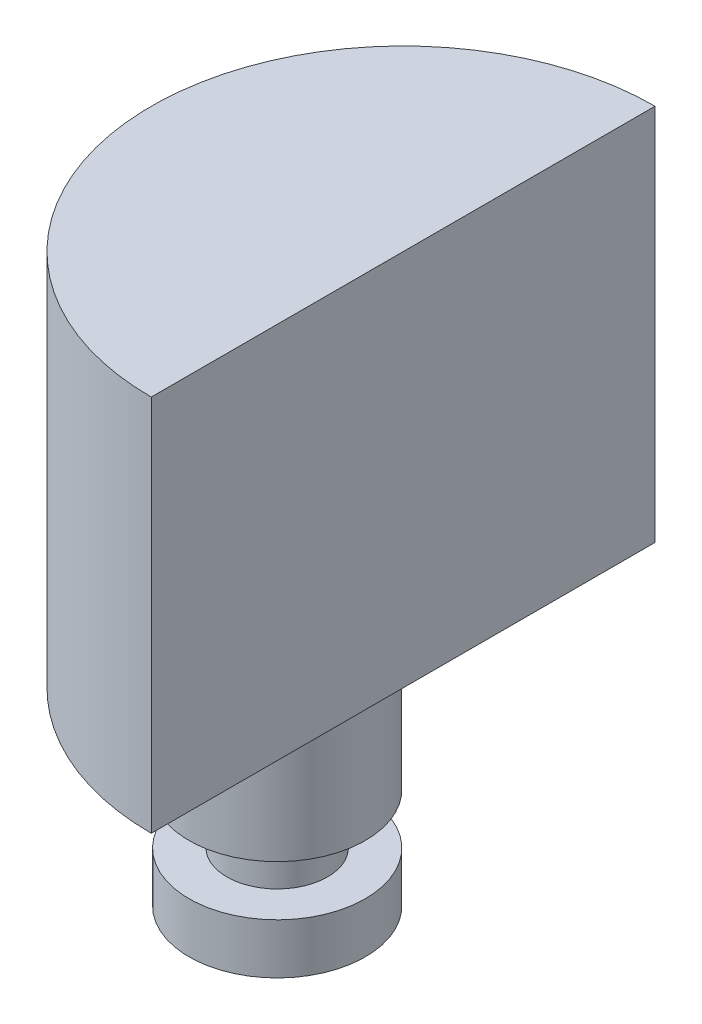
SolidWorks part; units mm, degrees
ref_plane "Alzado" through (0, 0, 0) normal (0, 0, 1) x (1, 0, 0)
ref_plane "Planta" through (0, 0, 0) normal (0, 1, 0) x (1, 0, 0)
ref_plane "Vista lateral" through (0, 0, 0) normal (1, 0, 0) x (0, 0, -1)
sketch "Croquis2" plane through (0, 0, 0) normal (0, 1, 0) x (1, 0, 0)
  line L0 (0, 10) -> (0, -10)
  arc A0 (0, 10) -> (0, -10) centre (0, 0) ccw
  point P3 (0, 0)
  dimension "D1" = 20
extrude "Saliente-Extruir1" add sketch "Croquis2" along normal blind 15
sketch "Croquis3" plane through (0, 0, 0) normal (0, -1, 0) x (1, 0, 0)
  line L0 (0, 0) -> (-10, 0) construction
  arc A0 (0, 10) -> (0, -10) centre (0, 0) ccw construction
  circle A1 centre (-5, 0) radius 3.5
  dimension "D1" = 7
extrude "Saliente-Extruir2" add sketch "Croquis3" along normal blind 6
sketch "Croquis5" plane through (0, -6, 0) normal (0, -1, 0) x (1, 0, 0)
  circle A0 centre (-5, 0) radius 2
  dimension "D1" = 4
extrude "Saliente-Extruir4" add sketch "Croquis5" along normal blind 2
sketch "Croquis7" plane through (0, -8, 0) normal (0, -1, 0) x (1, 0, 0)
  circle A0 centre (-5, 0) radius 3.5
  circle A1 centre (-5, 0) radius 3.5 construction
  point P3 (-5, 0)
extrude "Saliente-Extruir5" add sketch "Croquis7" along normal blind 2
